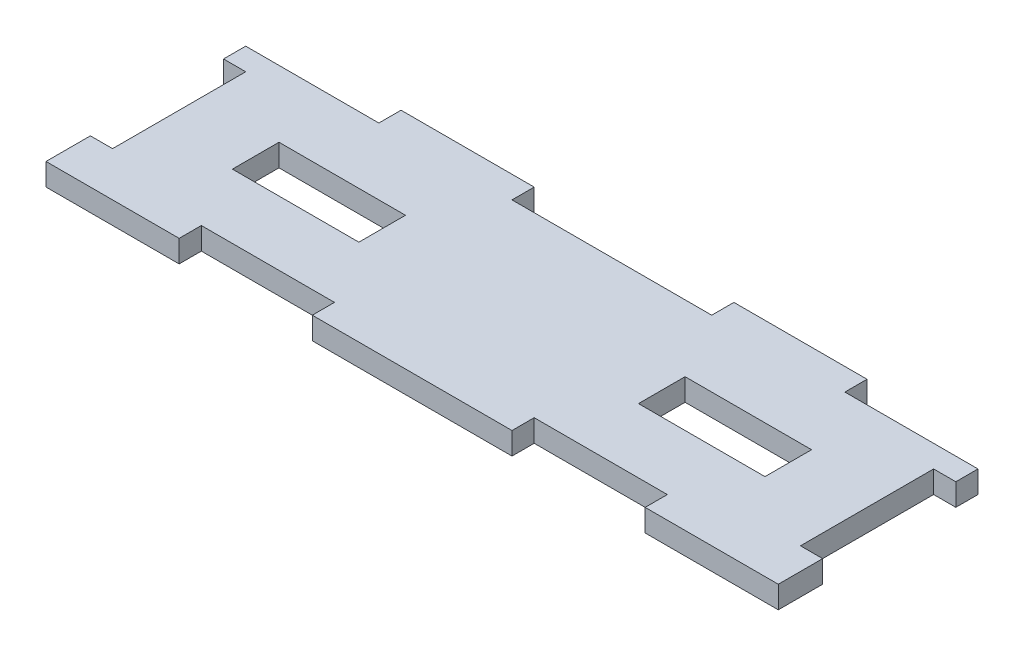
SolidWorks part; units mm, degrees
ref_plane "Front Plane" through (0, 0, 0) normal (0, 0, 1) x (1, 0, 0)
ref_plane "Top Plane" through (0, 0, 0) normal (0, 1, 0) x (1, 0, 0)
ref_plane "Right Plane" through (0, 0, 0) normal (1, 0, 0) x (0, 0, -1)
sketch "Sketch1" plane through (0, 0, 0) normal (0, 1, 0) x (1, 0, 0)
  line L0 (0, 40) -> (0, 45)
  line L1 (0, 0) -> (30, 0)
  line L2 (0, 10) -> (0, 0)
  line L3 (0, 45) -> (30, 45)
  line L4 (165, 10) -> (165, 0)
  line L5 (0, 40) -> (5, 40)
  line L7 (0, 10) -> (5, 10)
  line L8 (5, 40) -> (5, 10)
  line L9 (22.5, 30) -> (51, 30)
  line L10 (165, 40) -> (165, 45)
  line L11 (22.5, 30) -> (22.5, 19.5)
  line L12 (22.5, 19.5) -> (51, 19.5)
  line L13 (51, 30) -> (51, 19.5)
  line L14 (60, 45) -> (105, 45)
  line L15 (114, 30) -> (142.5, 30)
  line L16 (114, 30) -> (114, 19.5)
  line L17 (165, 10) -> (160, 10)
  line L18 (114, 19.5) -> (142.5, 19.5)
  line L19 (165, 40) -> (160, 40)
  line L20 (160, 10) -> (160, 40)
  line L21 (135, 45) -> (165, 45)
  line L22 (30, 45) -> (30, 50)
  line L23 (30, 50) -> (60, 50)
  line L24 (60, 45) -> (60, 50)
  line L25 (60, 0) -> (105, 0)
  line L26 (105, 45) -> (105, 50)
  line L27 (105, 50) -> (135, 50)
  line L28 (135, 45) -> (135, 50)
  line L29 (135, 0) -> (165, 0)
  line L30 (30, 0) -> (30, 5)
  line L31 (30, 5) -> (60, 5)
  line L32 (60, 0) -> (60, 5)
  line L33 (142.5, 30) -> (142.5, 19.5)
  line L34 (105, 0) -> (105, 5)
  line L35 (105, 5) -> (135, 5)
  line L36 (135, 0) -> (135, 5)
  dimension "D3" = 5
  dimension "D4" = 30
  dimension "D5" = 5
  dimension "D6" = 5
  dimension "D7" = 45
  dimension "D8" = 165
  dimension "D9" = 45
  dimension "D10" = 155
  dimension "D11" = 30
  dimension "D12" = 5
  dimension "D13" = 30
  dimension "D14" = 30
  dimension "D15" = 30
  dimension "D16" = 30
  dimension "D17" = 5
  dimension "D18" = 5
  dimension "D19" = 30
  dimension "D20" = 5
  dimension "D21" = 5
  dimension "D22" = 30
  dimension "D23" = 30
  dimension "D24" = 165
  dimension "D25" = 30
  dimension "D26" = 120
  dimension "D27" = 10.5
  dimension "D28" = 10.5
  dimension "D29" = 28.5
  dimension "D30" = 28.5
  dimension "D31" = 17.5
  dimension "D32" = 15
  dimension "D33" = 15
extrude "Boss-Extrude1" add sketch "Sketch1" along normal blind 5
